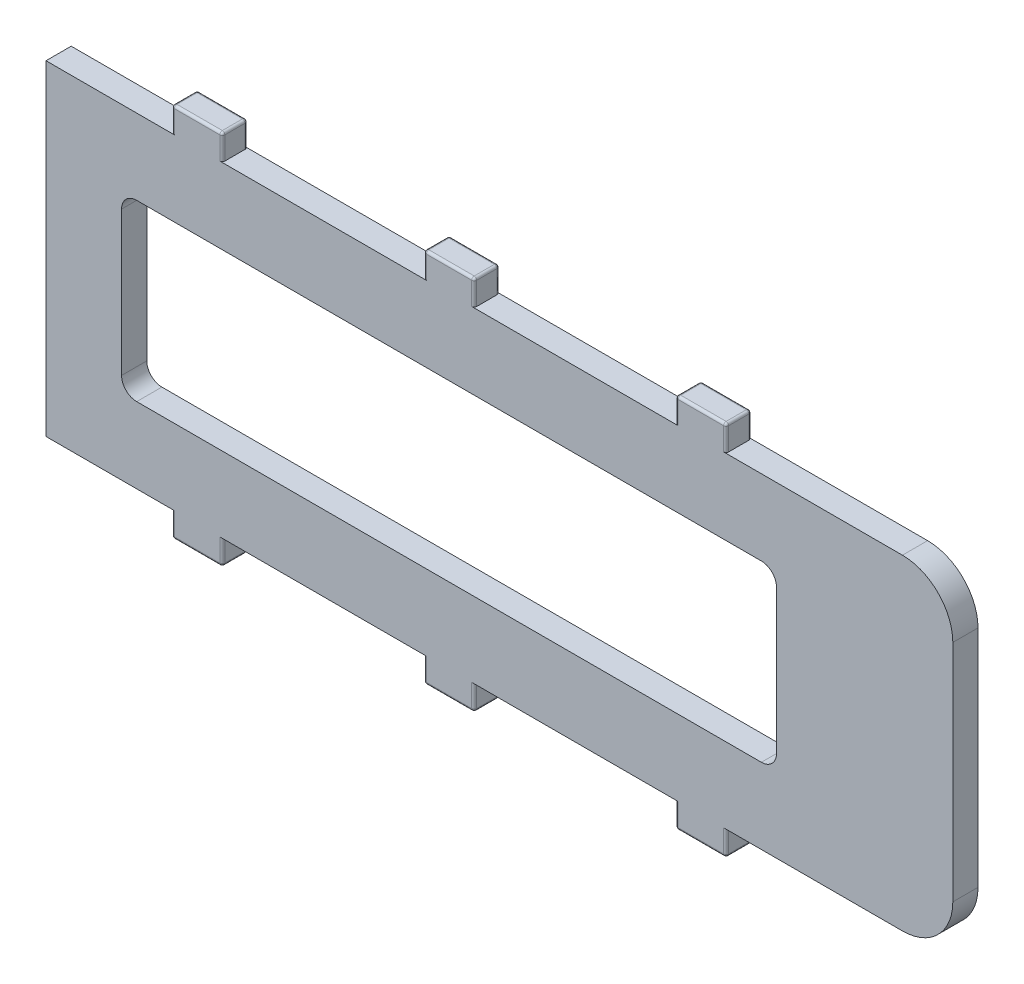
SolidWorks part; units mm, degrees
ref_plane "Alzado" through (0, 0, 0) normal (0, 0, 1) x (1, 0, 0)
ref_plane "Planta" through (0, 0, 0) normal (0, 1, 0) x (1, 0, 0)
ref_plane "Vista lateral" through (0, 0, 0) normal (1, 0, 0) x (0, 0, -1)
sketch "Croquis1" plane through (0, 0, 0) normal (0, 0, 1) x (1, 0, 0)
  line L1 (90, -32.3) -> (-90, -32.3)
  line L2 (90, -32.3) -> (90, 32.3)
  line L3 (90, 32.3) -> (-90, 32.3)
  line L4 (-90, -32.3) -> (-90, 32.3)
  line L5 (90, -32.3) -> (-90, 32.3) construction
  line L6 (90, 32.3) -> (-90, -32.3) construction
  point P0 (0, 0)
  dimension "D1" = 64.6
  dimension "D2" = 180
extrude "Saliente-Extruir1" add sketch "Croquis1" along normal blind 5
sketch "Croquis2" plane through (0, 32.3, 0) normal (0, 1, 0) x (1, 0, 0)
  line L0 (90, 0) -> (-90, 0) construction
  line L1 (-65, 0) -> (-55, 0)
  line L2 (-65, 0) -> (-65, -5)
  line L3 (-65, -5) -> (-55, -5)
  line L4 (-55, 0) -> (-55, -5)
  line L5 (90, -5) -> (-90, -5) construction
  line L6 (-90, -5) -> (-90, 0) construction
  line L7 (-15, 0) -> (-5, 0)
  line L8 (-15, 0) -> (-15, -5)
  line L9 (-15, -5) -> (-5, -5)
  line L10 (-5, 0) -> (-5, -5)
  line L11 (35, 0) -> (45, 0)
  line L12 (35, 0) -> (35, -5)
  line L13 (35, -5) -> (45, -5)
  line L14 (45, 0) -> (45, -5)
  point P16 (-60, -5)
  point P17 (-10, -5)
  point P18 (40, -5)
  dimension "D1" = 10
  dimension "D2" = 10
  dimension "D3" = 10
  dimension "D4" = 50
  dimension "D5" = 50
  dimension "D6" = 30
extrude "Saliente-Extruir2" add sketch "Croquis2" along normal blind 5
fillet "Redondeo1" radius 0.5 24 edges at (40, 37.3, 0) (45, 37.3, 2.5) (40, 37.3, 5) (35, 37.3, 2.5) (-10, 37.3, 0) (-5, 37.3, 2.5) (-10, 37.3, 5) (-15, 37.3, 2.5) (-60, 37.3, 0) (-55, 37.3, 2.5) (-60, 37.3, 5) (-65, 37.3, 2.5) (35, 34.8, 5) (45, 34.8, 5) (35, 34.8, 0) (45, 34.8, 0) (-5, 34.8, 0) (-5, 34.8, 5) (-15, 34.8, 5) (-15, 34.8, 0) (-65, 34.8, 5) (-55, 34.8, 5) (-55, 34.8, 0) (-65, 34.8, 0)
mirror "Simetría1" about plane through (0, 0, 0) normal (0, 1, 0) of "Saliente-Extruir2", "Redondeo1"
fillet "Redondeo2" radius 10 2 edges at (90, -32.3, 2.5) (90, 32.3, 2.5)
sketch "Croquis3" plane through (0, 0, 0) normal (0, 0, -1) x (-1, 0, 0)
  line L0 (90, 32.3) -> (90, -32.3) construction
  line L1 (-55, 17.3) -> (75, 17.3)
  line L2 (-55, 17.3) -> (-55, -17.3)
  line L3 (-55, -17.3) -> (75, -17.3)
  line L4 (75, 17.3) -> (75, -17.3)
  line L5 (64.5, 32.3) -> (90, 32.3) construction
  line L6 (90, -32.3) -> (64.5, -32.3) construction
  dimension "D1" = 15
  dimension "D2" = 15
  dimension "D3" = 15
  dimension "D4" = 145
extrude "Cortar-Extruir1" cut sketch "Croquis3" against normal blind 5
fillet "Redondeo3" radius 3 4 edges at (55, -17.3, 2.5) (-75, -17.3, 2.5) (-75, 17.3, 2.5) (55, 17.3, 2.5)
